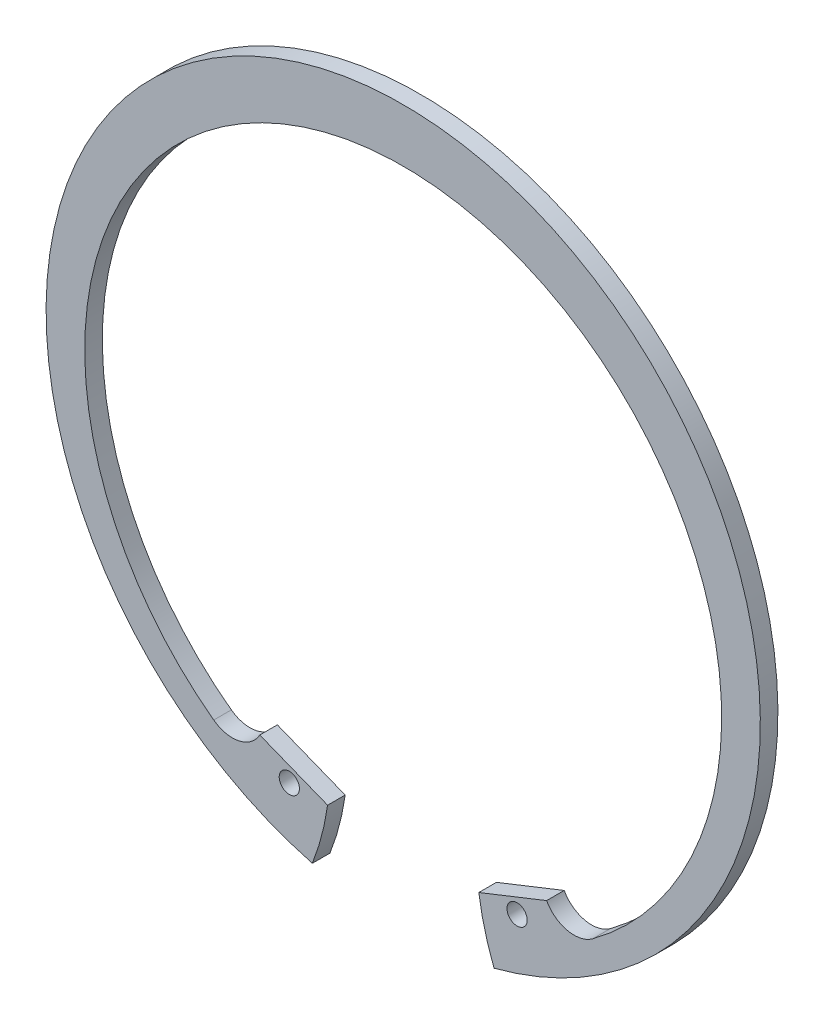
SolidWorks part; units mm, degrees
material "1023 Carbon Steel Sheet (SS)"
ref_plane "Front Plane" through (0, 0, 0) normal (0, 0, 1) x (1, 0, 0)
ref_plane "Top Plane" through (0, 0, 0) normal (0, 1, 0) x (1, 0, 0)
ref_plane "Right Plane" through (0, 0, 0) normal (1, 0, 0) x (0, 0, -1)
sketch "Sketch1" plane through (0, 0, 0) normal (0, 0, 1) x (1, 0, 0)
  line L0 (0, 56.1848) -> (0, 47.8028) construction
  line L1 (-32.2263, -46.0239) -> (-29.8078, -42.57) construction
  line L2 (0, 0) -> (0, -56.1848) construction
  line L3 (-11.6586, -45.3109) -> (-14.0004, -54.4125) construction
  line L4 (-11.6586, -45.3109) -> (-14.8336, -45.3109) construction
  circle A0 centre (0, 0) radius 53.848 construction
  circle A1 centre (0, 0) radius 56.1848 construction
  circle A2 centre (0, 0) radius 50.8 construction
  dimension "Ring OD" = 112.3696
  dimension "For ID" = 101.6
  dimension "Maximum Section" = 8.382
  dimension "D1" = 145
  dimension "Minimum Section" = 4.2164
  dimension "Gap Width" = 23.3172
  dimension "Lug Height" = 9.398
  dimension "Hole Diameter" = 3.175
sketch "Sketch2" plane through (0, 0, 0) normal (1, 0, 0) x (0, 0, -1)
  line L0 (-1.524, 56.1848) -> (1.524, 56.1848) construction
  line L1 (-1.3843, -56.1848) -> (1.3843, -56.1848) construction
  point P3 (0, 56.1848)
  point P7 (0, -56.1848)
  point P8 (-1.3843, -56.1848)
  point P10 (1.3843, -56.1848)
  point P11 (-1.524, 56.1848)
  point P12 (1.524, 56.1848)
  dimension "For Groove Width" = 3.048
  dimension "Ring Thickness" = 2.7686
sketch "Sketch3" plane through (0, 0, 0) normal (0, 0, 1) x (1, 0, 0)
  line L0 (-14.0004, -54.4125) -> (-11.6586, -45.3109)
  line L1 (-11.6586, -45.3109) -> (-22.5633, -40.9866)
  line L2 (0, 0) -> (-17.111, -43.1488) construction
  line L3 (-29.8078, -42.57) -> (29.8078, -42.57) construction
  line L4 (0, 0) -> (0, -56.1848) construction
  line L5 (-22.5633, -40.9866) -> (0, 0) construction
  line L6 (-17.111, -43.1488) -> (-17.9187, -45.1856) construction
  line L7 (-17.9187, -45.1856) -> (-18.7264, -47.2225) construction
  line L8 (0, 56.1848) -> (0, 47.8028) construction
  line L9 (11.6586, -45.3109) -> (22.5633, -40.9866)
  line L10 (14.0004, -54.4125) -> (11.6586, -45.3109)
  arc A0 (-14.0004, -54.4125) -> (14.0004, -54.4125) centre (0, 0) cw
  circle A1 centre (0, 0) radius 56.1848 construction
  arc A2 (-29.8078, -42.57) -> (29.8078, -42.57) centre (0, -2.2994) cw
  arc A3 (-29.8078, -42.57) -> (-22.5633, -40.9866) centre (-26.8778, -38.6115) ccw
  circle A4 centre (-17.9187, -45.1856) radius 1.5875
  circle A5 centre (0, 0) radius 51.9684 construction
  arc A6 (29.8078, -42.57) -> (22.5633, -40.9866) centre (26.8778, -38.6115) cw
  circle A7 centre (17.9187, -45.1856) radius 1.5875
  circle A8 centre (0, 0) radius 50.8 construction
  point P3 (0, -42.57)
  dimension "D1" = 3.175
extrude "Boss-Extrude1" add sketch "Sketch3" against normal up to vertex (1.3843 mm away) and the other way up to vertex (1.3843 mm away) up to point (0, -56.1848, -1.3843) other way up to point (0, -56.1848, 1.3843)
sketch "Sketch4" plane through (0, 0, 0) normal (0, 0, 1) x (1, 0, 0)
  line L0 (-11.6586, -45.3109) -> (-22.5633, -40.9866) construction
  line L1 (-11.6586, -45.3109) -> (-14.0004, -54.4125) construction
  line L2 (-14.2935, -54.3362) -> (-11.8947, -45.2173) construction
  line L3 (-11.8947, -45.2173) -> (0, 0) construction
  line L4 (-14.2935, -54.3362) -> (-14.2935, -68.6298)
  line L5 (-14.2935, -68.6298) -> (0, -68.6298)
  line L6 (0, -68.6298) -> (0, -56.1848)
  line L7 (0, -56.1848) -> (0, -45.2173)
  line L8 (0, 0) -> (0, -56.1848) construction
  line L9 (0, -45.2173) -> (-11.8947, -45.2173)
  arc A0 (-11.8947, -45.2173) -> (-14.2935, -54.3362) centre (-51.7862, -39.5986) cw
  circle A1 centre (0, 0) radius 56.1848 construction
  dimension "D1" = 0.254
extrude "Cut-Extrude1" cut sketch "Sketch4" against normal through all both and the other way through all
mirror "Mirror1" about plane through (0, 0, 0) normal (1, 0, 0) of "Cut-Extrude1"
equation "\"D1@Sketch3\"=\"Hole Diameter@Sketch1\""
